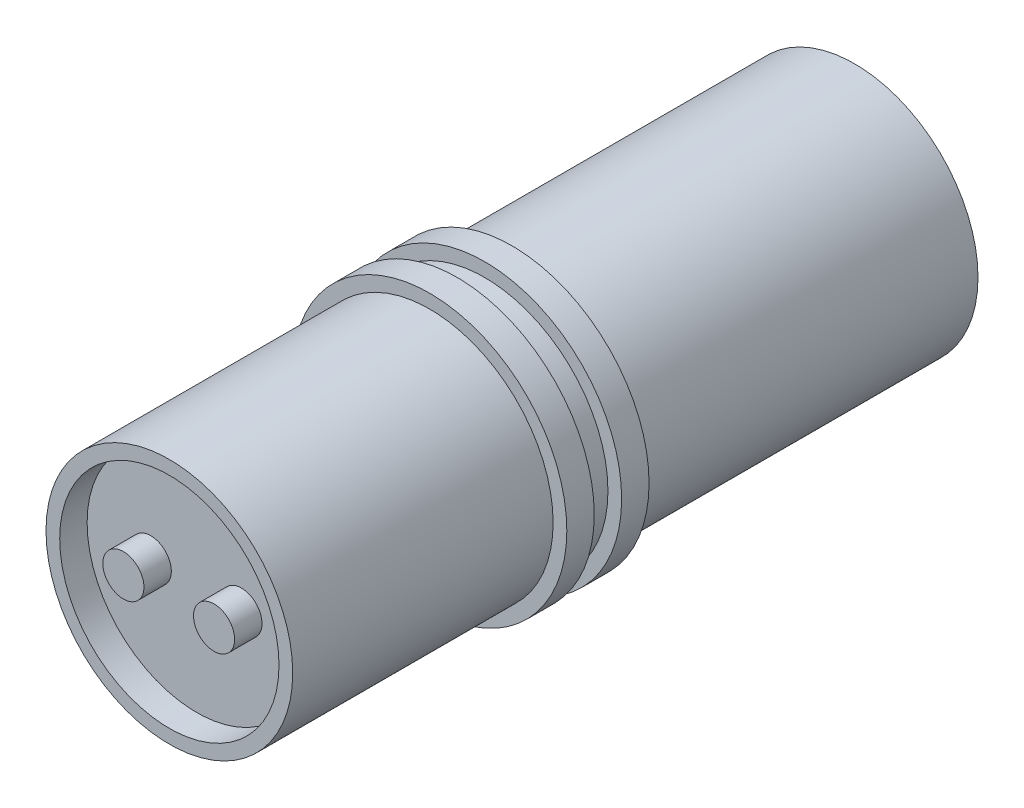
SolidWorks part; units mm, degrees
ref_plane "Front Plane" through (0, 0, 0) normal (0, 0, 1) x (1, 0, 0)
ref_plane "Top Plane" through (0, 0, 0) normal (0, 1, 0) x (1, 0, 0)
ref_plane "Right Plane" through (0, 0, 0) normal (1, 0, 0) x (0, 0, -1)
sketch "Sketch1" plane through (0, 0, 0) normal (0, 0, 1) x (1, 0, 0)
  circle A0 centre (0, 0) radius 9
  dimension "D1" = 18
extrude "Boss-Extrude1" add sketch "Sketch1" along normal blind 25
sketch "Sketch3" plane through (0, 0, 25) normal (0, 0, 1) x (1, 0, 0)
  circle A0 centre (0, 0) radius 10
  dimension "D1" = 20
extrude "Boss-Extrude2" add sketch "Sketch3" along normal blind 2
sketch "Sketch4" plane through (0, 0, 27) normal (0, 0, 1) x (1, 0, 0)
  circle A0 centre (0, 0) radius 9
  dimension "D1" = 18
extrude "Boss-Extrude3" add sketch "Sketch4" along normal blind 2
sketch "Sketch5" plane through (0, 0, 29) normal (0, 0, 1) x (1, 0, 0)
  circle A0 centre (0, 0) radius 10
  dimension "D1" = 20
extrude "Boss-Extrude4" add sketch "Sketch5" along normal blind 2
sketch "Sketch6" plane through (0, 0, 31) normal (0, 0, 1) x (1, 0, 0)
  circle A0 centre (0, 0) radius 9
  dimension "D1" = 18
extrude "Boss-Extrude5" add sketch "Sketch6" along normal blind 19
sketch "Sketch7" plane through (0, 0, 50) normal (0, 0, 1) x (1, 0, 0)
  circle A0 centre (0, 0) radius 8
  dimension "D1" = 16
extrude "Cut-Extrude1" cut sketch "Sketch7" against normal blind 2
sketch "Sketch8" plane through (0, 0, 48) normal (0, 0, 1) x (1, 0, 0)
  circle A0 centre (-3.3546, 0) radius 1.5
  circle A1 centre (3.2626, 0) radius 1.5
  dimension "D1" = 3
  dimension "D2" = 3
extrude "Boss-Extrude6" add sketch "Sketch8" along normal blind 2
sketch "Sketch9" plane through (0, 0, 0) normal (0, 0, -1) x (-1, 0, 0)
  line L0 (1.7115, 4.4792) -> (5.1391, 0) construction
  line L1 (2.6306, 5.1825) -> (6.0582, 0.7033)
  line L2 (0.7924, 3.7759) -> (4.22, -0.7033)
  arc A0 (2.6306, 5.1825) -> (0.7924, 3.7759) centre (1.7115, 4.4792) ccw
  arc A1 (4.22, -0.7033) -> (6.0582, 0.7033) centre (5.1391, 0) ccw
  point P2 (3.4253, 2.2396)
extrude "Boss-Extrude7" add sketch "Sketch9" along normal blind 2
